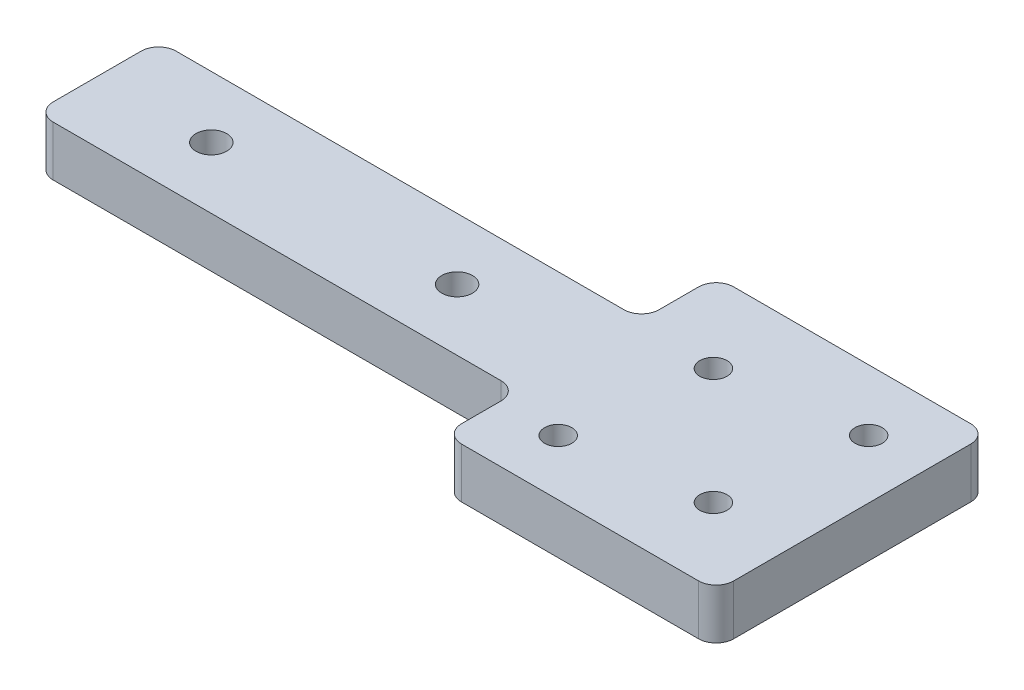
SolidWorks part; units mm, degrees
ref_plane "Front Plane" through (0, 0, 0) normal (0, 0, 1) x (1, 0, 0)
ref_plane "Top Plane" through (0, 0, 0) normal (0, 1, 0) x (1, 0, 0)
ref_plane "Right Plane" through (0, 0, 0) normal (1, 0, 0) x (0, 0, -1)
sketch "Sketch1" plane through (0, 0, 0) normal (0, 1, 0) x (1, 0, 0)
  line L1 (-4.4499, 7.3104) -> (50.5501, 7.3104)
  line L2 (-4.4499, 7.3104) -> (-4.4499, -6.6896)
  line L3 (-4.4499, -6.6896) -> (50.5501, -6.6896)
  line L4 (50.5501, 7.3104) -> (50.5501, -6.6896)
  dimension "D1" = 14
  dimension "D2" = 55
extrude "Boss-Extrude1" add sketch "Sketch1" along normal blind 5.715
sketch "Sketch2" plane through (0, 5.715, 0) normal (0, 1, 0) x (1, 0, 0)
  line L0 (-4.4499, 0.3104) -> (50.5501, 0.3104) construction
  line L1 (-4.4499, 7.3104) -> (-4.4499, -6.6896) construction
  line L2 (50.5501, -6.6896) -> (50.5501, 7.3104) construction
  circle A0 centre (8.5501, 0.3104) radius 1.75
  circle A1 centre (36.5501, 0.3104) radius 1.75
  dimension "D2" = 3.5
  dimension "D1" = 28
  dimension "D3" = 13
extrude "Cut-Extrude1" cut sketch "Sketch2" against normal through all
sketch "Sketch3" plane through (50.5501, 0, 0) normal (1, 0, 0) x (0, 0, -1)
  line L0 (-6.6896, 5.715) -> (7.3104, 5.715) construction
  line L1 (15.8104, 5.715) -> (-15.1896, 5.715)
  line L2 (15.8104, 5.715) -> (15.8104, 0)
  line L3 (15.8104, 0) -> (-15.1896, 0)
  line L4 (-15.1896, 5.715) -> (-15.1896, 0)
  line L5 (-6.6896, 0) -> (7.3104, 0) construction
  line L6 (0.3104, 5.715) -> (0.3104, 0) construction
  line L7 (-6.6896, 5.715) -> (-6.6896, 0) construction
  line L8 (7.3104, 5.715) -> (7.3104, 0) construction
  dimension "D1" = 31
extrude "Boss-Extrude2" add sketch "Sketch3" along normal blind 31
sketch "Sketch4" plane through (0, 5.715, 0) normal (0, 1, 0) x (1, 0, 0)
  line L0 (81.5501, 0) -> (-4.4499, 0) construction
  line L1 (81.5501, 15.8104) -> (81.5501, -15.1896) construction
  line L2 (66.0501, -15.1896) -> (66.0501, 15.8104) construction
  line L3 (81.5501, -15.1896) -> (50.5501, -15.1896) construction
  line L4 (81.5501, 15.8104) -> (50.5501, 15.8104) construction
  line L5 (59.4386, 6.6114) -> (66.0501, 0) construction
  line L6 (66.0501, 0) -> (74.8889, 8.8388) construction
  line L7 (-4.4499, 7.3104) -> (-4.4499, -6.6896) construction
  line L8 (66.0501, 0) -> (72.6615, -6.6114) construction
  line L9 (66.0501, 0) -> (57.2112, -8.8388) construction
  line L10 (50.5501, 15.8104) -> (50.5501, 7.3104) construction
  circle A0 centre (57.2112, -8.8388) radius 1.55
  circle A1 centre (59.4386, 6.6114) radius 1.55
  circle A2 centre (74.8889, 8.8388) radius 1.55
  circle A3 centre (72.6615, -6.6114) radius 1.55
  dimension "D1" = 3.1
  dimension "D2" = 25
  dimension "D3" = 45
  dimension "D4" = 18.7
extrude "Cut-Extrude2" cut sketch "Sketch4" against normal through all
fillet "Fillet1" radius 2 8 edges at (-4.4499, 2.8575, -7.3104) (-4.4499, 2.8575, 6.6896) (50.5501, 2.8575, -15.8104) (81.5501, 2.8575, -15.8104) (81.5501, 2.8575, 15.1896) (50.5501, 2.8575, 15.1896)
